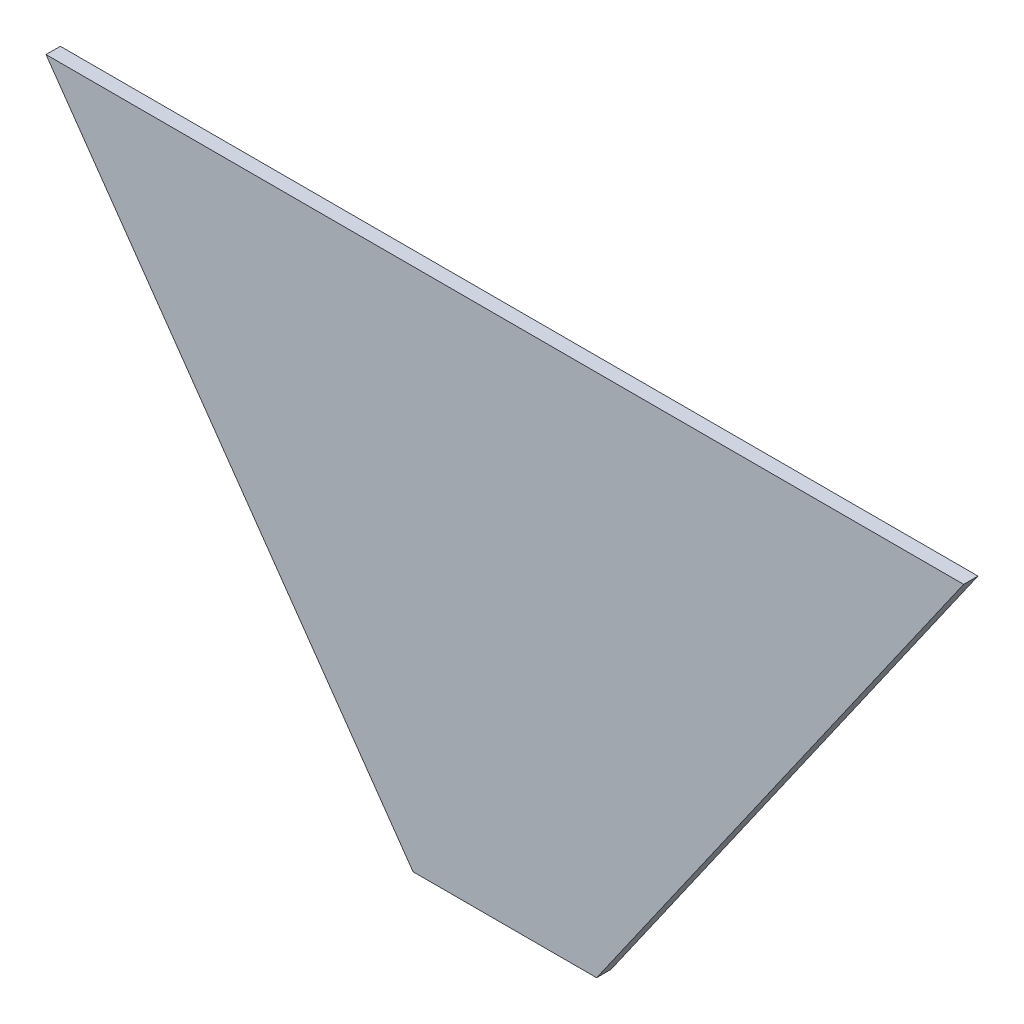
SolidWorks part; units mm, degrees
ref_plane "Front" through (0, 0, 0) normal (0, 0, 1) x (1, 0, 0)
ref_plane "Top" through (0, 0, 0) normal (0, 1, 0) x (1, 0, 0)
ref_plane "Right" through (0, 0, 0) normal (1, 0, 0) x (0, 0, -1)
sketch "Sketch1" plane through (0, 0, 0) normal (0, 0, 1) x (1, 0, 0)
  line L0 (-10.16, 0) -> (10.16, 0)
  line L1 (0, 0) -> (0, 58.0399) construction
  line L2 (50.8, 58.0399) -> (-50.8, 58.0399)
  line L3 (50.8, 58.0399) -> (10.16, 0)
  line L4 (-10.16, 0) -> (-50.8, 58.0399)
  dimension "D1" = 20.32
  dimension "D2" = 101.6
  dimension "D3" = 55
extrude "Boss-Extrude1" add sketch "Sketch1" along normal blind 1.5875
